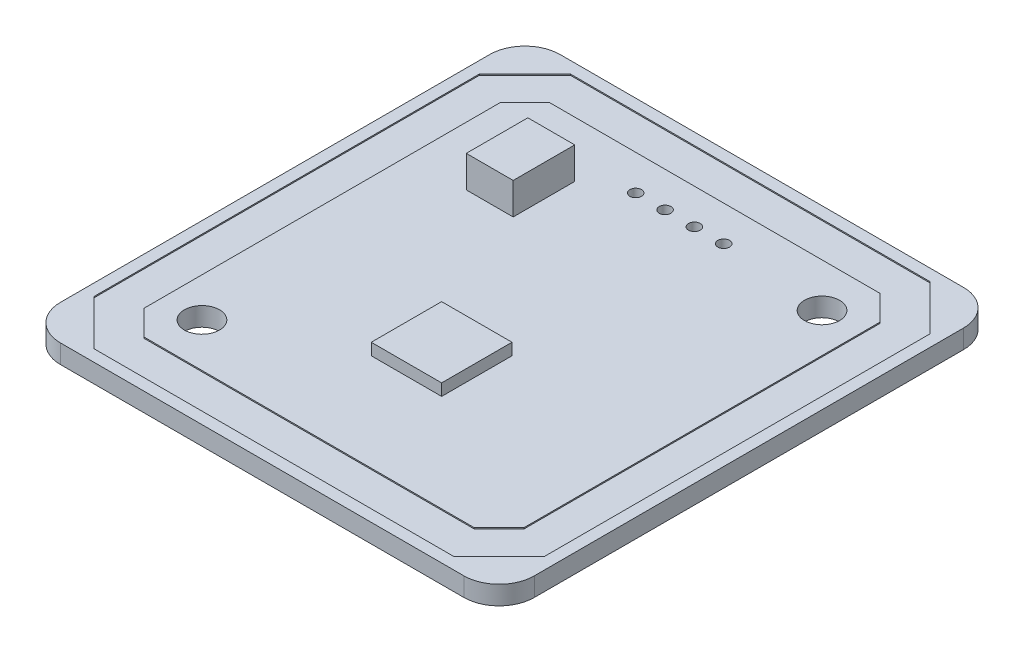
SolidWorks part; units mm, degrees
ref_plane "Front Plane" through (0, 0, 0) normal (0, 0, 1) x (1, 0, 0)
ref_plane "Top Plane" through (0, 0, 0) normal (0, 1, 0) x (1, 0, 0)
ref_plane "Right Plane" through (0, 0, 0) normal (1, 0, 0) x (0, 0, -1)
sketch "Sketch1" plane through (0, 0, 0) normal (0, 1, 0) x (1, 0, 0)
  line L1 (20.2, 21.3) -> (-20.2, 21.3)
  line L2 (20.2, 21.3) -> (20.2, -21.3)
  line L3 (20.2, -21.3) -> (-20.2, -21.3)
  line L4 (-20.2, 21.3) -> (-20.2, -21.3)
  line L5 (20.2, 21.3) -> (-20.2, -21.3) construction
  line L6 (20.2, -21.3) -> (-20.2, 21.3) construction
  point P0 (0, 0)
  dimension "D1" = 42.6
  dimension "D2" = 40.4
extrude "Boss-Extrude1" add sketch "Sketch1" along normal blind 1.6
sketch "Sketch2" plane through (0, 1.6, 0) normal (0, 1, 0) x (1, 0, 0)
  line L0 (-20.2, 0) -> (20.2, 0) construction
  line L1 (-20.2, 21.3) -> (-20.2, -21.3) construction
  line L2 (20.2, -21.3) -> (20.2, 21.3) construction
  line L3 (12.8679, 13.5686) -> (-12.8679, -13.5686) construction
  circle A0 centre (12.8679, 13.5686) radius 1.5
  circle A1 centre (-12.8679, -13.5686) radius 1.5
  point P10 (-13.261, -13.1847)
  dimension "D1" = 34.4
  dimension "D2" = 3
extrude "Cut-Extrude1" cut sketch "Sketch2" against normal through all
sketch "Sketch5" plane through (0, 1.6, 0) normal (0, 1, 0) x (1, 0, 0)
  line L0 (-14.7, 18.8) -> (-17.7, 15.8)
  line L1 (17.7, 15.8) -> (14.7, 18.8)
  line L2 (14.7, -18.8) -> (17.7, -15.8)
  line L3 (-17.7, -15.8) -> (-14.7, -18.8)
  line L8 (-17.7, 18.8) -> (-17.7, -18.8)
  line L9 (-17.7, -18.8) -> (17.7, -18.8)
  line L10 (17.7, -18.8) -> (17.7, 18.8)
  line L11 (17.7, 18.8) -> (-17.7, 18.8)
  line L12 (-17.7, 15.8) -> (-17.7, -15.8)
  line L13 (-14.7, -18.8) -> (14.7, -18.8)
  line L14 (17.7, -15.8) -> (17.7, 15.8)
  line L15 (14.7, 18.8) -> (-14.7, 18.8)
  point P0 (0, 0)
  dimension "D1" = 2.5
extrude "Cut-Extrude-Thin2" cut sketch "Sketch5" against normal blind 0.1 thin thin type mid plane wall 3
fillet "Fillet1" radius 3 4 edges at (20.2, 0.8, -21.3) (20.2, 0.8, 21.3) (-20.2, 0.8, 21.3) (-20.2, 0.8, -21.3)
sketch "Sketch3" plane through (0, 1.6, 0) normal (0, 1, 0) x (1, 0, 0)
  line L0 (-20.2, 18.3) -> (-20.2, -18.3) construction
  line L1 (-7.2, 12.55) -> (-11.2, 12.55)
  line L2 (-7.2, 12.55) -> (-7.2, 7.3)
  line L3 (-7.2, 7.3) -> (-11.2, 7.3)
  line L4 (-11.2, 12.55) -> (-11.2, 7.3)
  line L5 (-7.2, 12.55) -> (-11.2, 7.3) construction
  line L6 (-7.2, 7.3) -> (-11.2, 12.55) construction
  line L7 (17.2, 21.3) -> (-17.2, 21.3) construction
  point P0 (-9.2, 9.925)
  dimension "D1" = 4
  dimension "D2" = 13
  dimension "D3" = 5.25
  dimension "D4" = 14
extrude "Boss-Extrude2" add sketch "Sketch3" along normal blind 2.7
sketch "Sketch4" plane through (0, 1.6, 0) normal (0, 1, 0) x (1, 0, 0)
  line L1 (3, -9) -> (-3, -9)
  line L2 (3, -9) -> (3, -3)
  line L3 (3, -3) -> (-3, -3)
  line L4 (-3, -9) -> (-3, -3)
  line L5 (3, -9) -> (-3, -3) construction
  line L6 (3, -3) -> (-3, -9) construction
  point P0 (0, -6)
  point P5 (0, 0)
  dimension "D1" = 6
  dimension "D2" = 6
extrude "Boss-Extrude3" add sketch "Sketch4" along normal blind 1
sketch "Sketch6" plane through (0, 1.6, 0) normal (0, 1, 0) x (1, 0, 0)
  line L0 (0, 0) -> (0, 21.3) construction
  line L1 (17.2, 21.3) -> (-17.2, 21.3) construction
  line L2 (-1.25, 14.3) -> (1.25, 14.3) construction
  line L3 (-3.75, 14.3) -> (-1.25, 14.3) construction
  circle A0 centre (-3.75, 14.3) radius 0.5
  circle A1 centre (-1.25, 14.3) radius 0.5
  circle A2 centre (1.25, 14.3) radius 0.5
  circle A3 centre (3.75, 14.3) radius 0.5
  point P13 (-1.1262, 14.0771)
  dimension "D2" = 1
  dimension "D1" = 7
  dimension "D3" = 2.5
extrude "Cut-Extrude2" cut sketch "Sketch6" against normal through all
